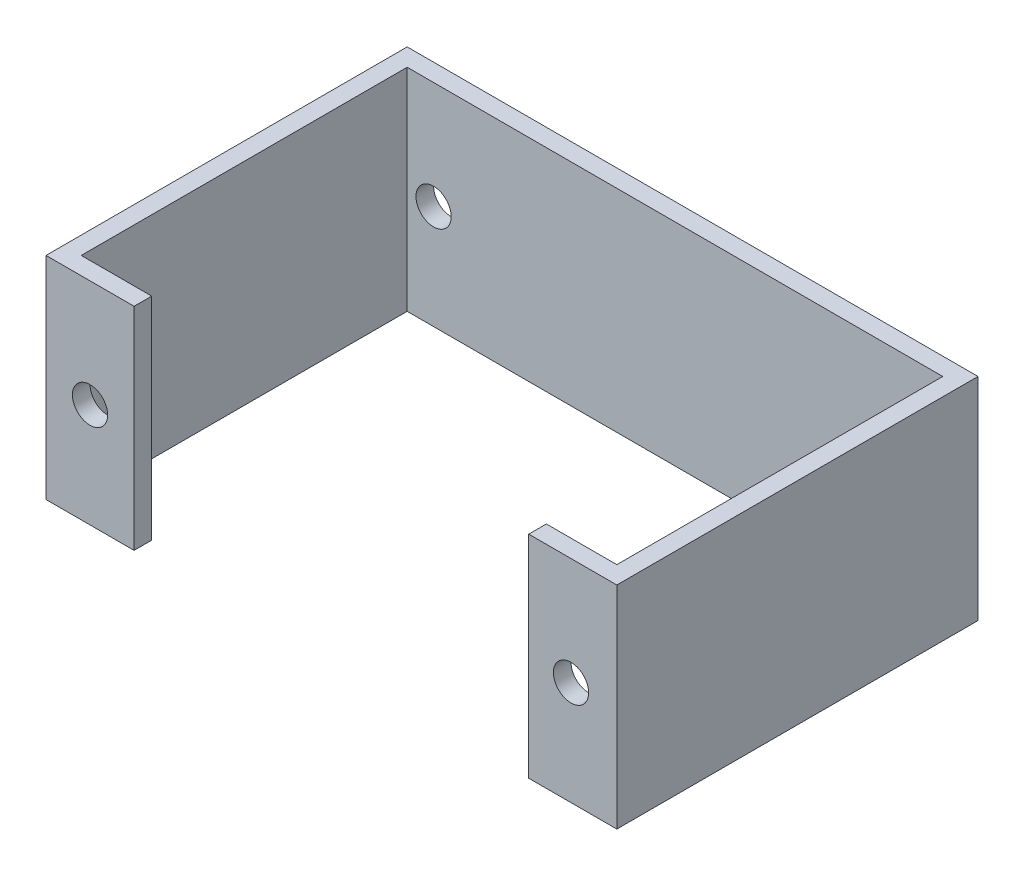
SolidWorks part; units mm, degrees
ref_plane "Front Plane" through (0, 0, 0) normal (0, 0, 1) x (1, 0, 0)
ref_plane "Top Plane" through (0, 0, 0) normal (0, 1, 0) x (1, 0, 0)
ref_plane "Right Plane" through (0, 0, 0) normal (1, 0, 0) x (0, 0, -1)
sketch "Sketch1" plane through (0, 0, 0) normal (0, 0, 1) x (1, 0, 0)
  line L1 (0, 0) -> (-5, 0)
  line L2 (0, 0) -> (0, 12)
  line L3 (0, 12) -> (-5, 12)
  line L4 (-5, 0) -> (-5, 12)
  line L5 (-5, 12) -> (-5.8, 12)
  line L6 (-5, 12) -> (-5, 0)
  line L7 (-5, 0) -> (-5.8, 0)
  line L8 (-5.8, 12) -> (-5.8, 0)
  dimension "D1" = 5
  dimension "D2" = 12
  dimension "D3" = 0.8
sketch "Sketch2" plane through (0, 0, 0) normal (0, 1, 0) x (1, 0, 0)
  line L1 (0, 0) -> (30.4, 0)
  line L2 (0, 0) -> (0, -18.5)
  line L4 (30.4, 0) -> (30.4, -18.5)
  line L5 (0, -18.5) -> (4, -18.5)
  line L6 (30.4, -18.5) -> (26.4, -18.5)
  point P5 (5, -18.5195)
  dimension "D1" = 30.4
  dimension "D2" = 18.5
  dimension "D3" = 4
  dimension "D4" = 4
extrude "Extrude-Thin1" add sketch "Sketch2" along normal blind 12 thin thin type one direction wall 1
sketch "Sketch4" plane through (0, 0, 19.5) normal (0, 0, 1) x (1, 0, 0)
  circle A0 centre (28.8, 5.9) radius 1
  circle A1 centre (1.5, 5.9) radius 1
  dimension "D1" = 2
  dimension "D2" = 2
extrude "Cut-Extrude2" cut sketch "Sketch4" against normal through all
